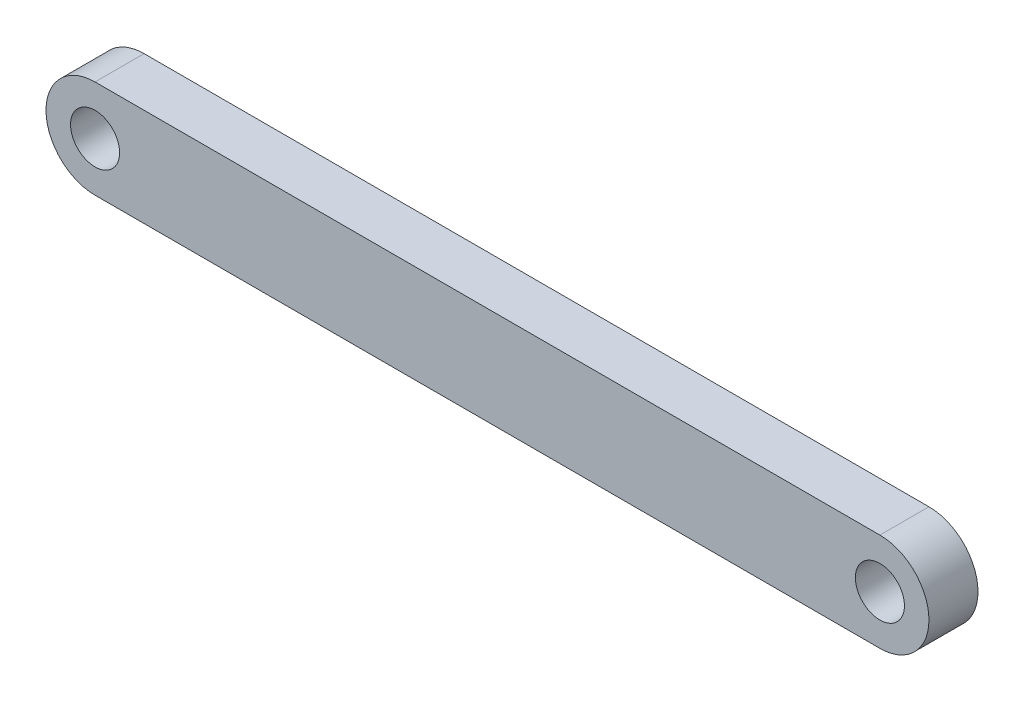
SolidWorks part; units mm, degrees
ref_plane "前视基准面" through (0, 0, 0) normal (0, 0, 1) x (1, 0, 0)
ref_plane "上视基准面" through (0, 0, 0) normal (0, 1, 0) x (1, 0, 0)
ref_plane "右视基准面" through (0, 0, 0) normal (1, 0, 0) x (0, 0, -1)
sketch "草图1" plane through (0, 0, 0) normal (0, 0, 1) x (1, 0, 0)
  line L1 (-54.1194, 6.2956) -> (105.8806, 6.2956)
  line L3 (-54.1194, -13.7044) -> (105.8806, -13.7044)
  arc A1 (-54.1194, 6.2956) -> (-54.1194, -13.7044) centre (-54.1194, -3.7044) ccw
  arc A2 (105.8806, 6.2956) -> (105.8806, -13.7044) centre (105.8806, -3.7044) cw
  point P7 (105.8806, -1.757)
extrude "凸台-拉伸1" add sketch "草图1" along normal blind 10
sketch "草图2" plane through (0, 0, 10) normal (0, 0, 1) x (1, 0, 0)
  circle A0 centre (105.8806, -3.7044) radius 5
  circle A1 centre (-54.1194, -3.7044) radius 5
extrude "切除-拉伸1" cut sketch "草图2" against normal blind 10
